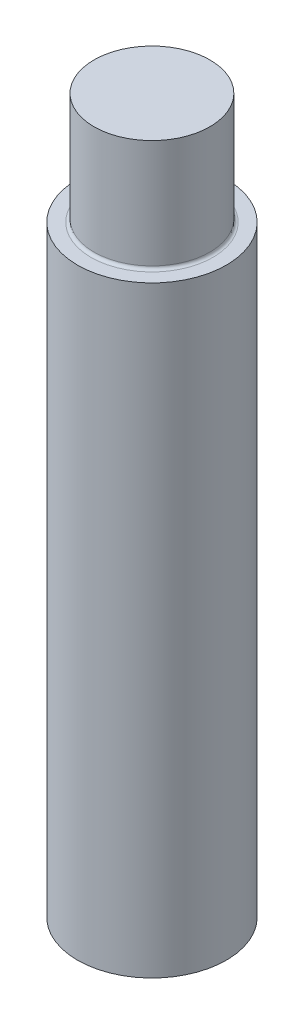
SolidWorks part; units mm, degrees
ref_plane "Alzado" through (0, 0, 0) normal (0, 0, 1) x (1, 0, 0)
ref_plane "Planta" through (0, 0, 0) normal (0, 1, 0) x (1, 0, 0)
ref_plane "Vista lateral" through (0, 0, 0) normal (1, 0, 0) x (0, 0, -1)
sketch "Croquis2" plane through (0, 0, 0) normal (0, 1, 0) x (1, 0, 0)
  circle A0 centre (0, 0) radius 12.2
  dimension "D1" = 24.4
extrude "Saliente-Extruir1" add sketch "Croquis2" along normal blind 98.7
sketch "Croquis3" plane through (0, 98.7, 0) normal (0, 1, 0) x (1, 0, 0)
  circle A0 centre (0, 0) radius 9.5
  dimension "D1" = 19
extrude "Saliente-Extruir2" add sketch "Croquis3" along normal blind 18.3
fillet "Redondeo2" radius 0.5 1 edges at (0, 98.7, 9.5)
